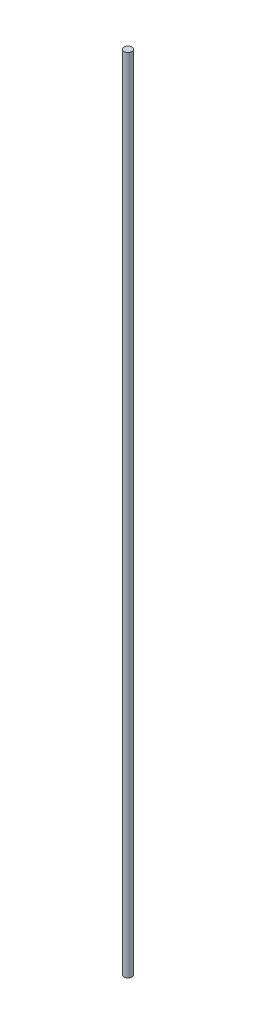
SolidWorks part; units mm, degrees
ref_plane "Спереди" through (0, 0, 0) normal (0, 0, 1) x (1, 0, 0)
ref_plane "Сверху" through (0, 0, 0) normal (0, 1, 0) x (1, 0, 0)
ref_plane "Справа" through (0, 0, 0) normal (1, 0, 0) x (0, 0, -1)
sketch "Эскиз1" plane through (0, 0, 0) normal (0, 1, 0) x (1, 0, 0)
  circle A0 centre (0, 0) radius 4
  dimension "D1" = 8
extrude "Бобышка-Вытянуть1" add sketch "Эскиз1" along normal blind 815
